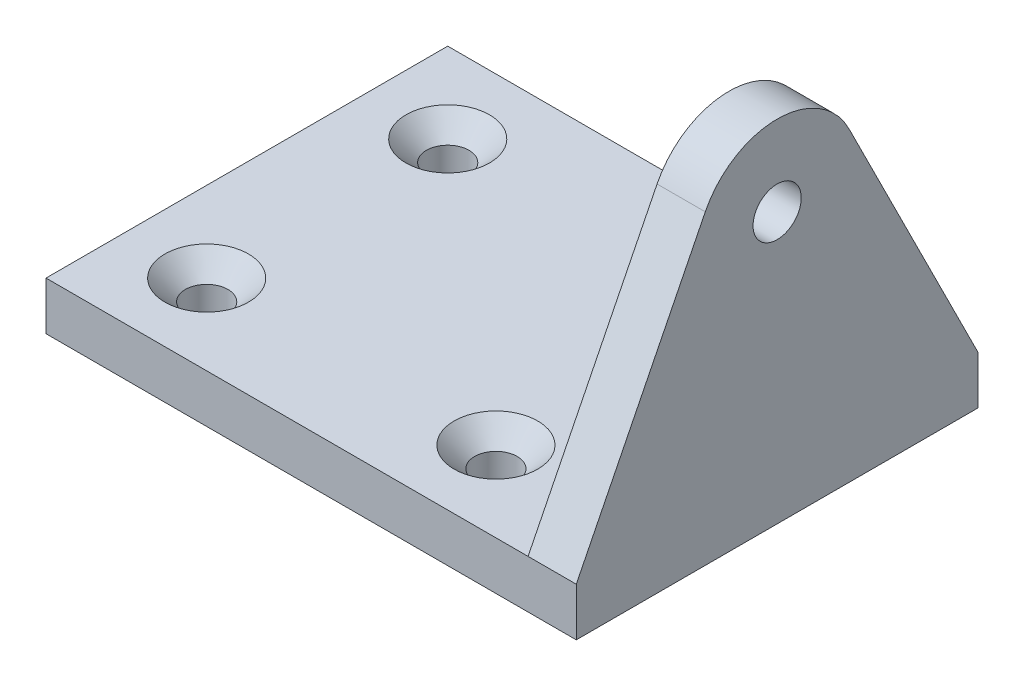
SolidWorks part; units mm, degrees
ref_plane "Front Plane" through (0, 0, 0) normal (0, 0, 1) x (1, 0, 0)
ref_plane "Top Plane" through (0, 0, 0) normal (0, 1, 0) x (1, 0, 0)
ref_plane "Right Plane" through (0, 0, 0) normal (1, 0, 0) x (0, 0, -1)
sketch "Sketch1" plane through (0, 0, 0) normal (0, 1, 0) x (1, 0, 0)
  line L1 (-30, 25) -> (30, 25)
  line L2 (-30, 25) -> (-30, -25)
  line L3 (-30, -25) -> (30, -25)
  line L4 (30, 25) -> (30, -25)
  line L5 (-30, 25) -> (30, -25) construction
  line L6 (-30, -25) -> (30, 25) construction
  point P0 (0, 0)
  dimension "D1" = 60
  dimension "D2" = 50
extrude "Boss-Extrude1" add sketch "Sketch1" along normal blind 6
hole_wizard "CSK for M5 Countersunk Raised Head Screw1" positions "Sketch3" profile "Sketch4" countersink size "M5" standard "ISO" end condition through all
sketch "Sketch3" plane through (0, 6, 0) normal (0, 1, 0) x (1, 0, 0)
  line L0 (-30, 0) -> (0, 0) construction
  line L1 (-30, 25) -> (-30, -25) construction
  point P0 (-20, -15)
  point P2 (16, -15)
  point P22 (0, 0)
  point P23 (16, 15)
  point P24 (-20, 15)
  dimension "D1" = 20
  dimension "D2" = 36
  dimension "D3" = 15
sketch "Sketch4" plane through (-20, 6, 15) normal (1, 0, 0) x (0, 0, 1)
  line L0 (0, 0) -> (0, 6)
  line L1 (0, 6) -> (2.65, 6)
  line L2 (2.65, 6) -> (2.65, 2.55)
  line L3 (2.65, 2.55) -> (5.2, 0)
  line L5 (5.2, 0) -> (0, 0)
  line L6 (-2.65, 2.55) -> (-5.2, 0) construction
  line L11 (0, -6.35) -> (0, 107.95) construction
  dimension "Thru Hole Dia." = 5.3
  dimension "Thru Hole Depth" = 6
  dimension "Near C'Sink Dia." = 10.4
  dimension "Near C'Sink Angle" = 90
sketch "Sketch5" plane through (30, 0, 0) normal (1, 0, 0) x (0, 0, -1)
  line L0 (-25, 6) -> (-8.9443, 38.1115)
  line L1 (8.9443, 38.1115) -> (25, 6)
  line L3 (-25, 6) -> (-25, 0)
  line L4 (-25, 0) -> (25, 0)
  line L5 (25, 0) -> (25, 6)
  arc A0 (8.9443, 38.1115) -> (-8.9443, 38.1115) centre (0, 33.6393) ccw
  point P7 (0, 56)
  dimension "D2" = 10
  dimension "D1" = 50
extrude "Boss-Extrude2" add sketch "Sketch5" along normal blind 6
sketch "Sketch6" plane through (36, 0, 0) normal (1, 0, 0) x (0, 0, -1)
  circle A0 centre (0, 33.6393) radius 3
  dimension "D1" = 6
extrude "Cut-Extrude1" cut sketch "Sketch6" against normal blind 6
